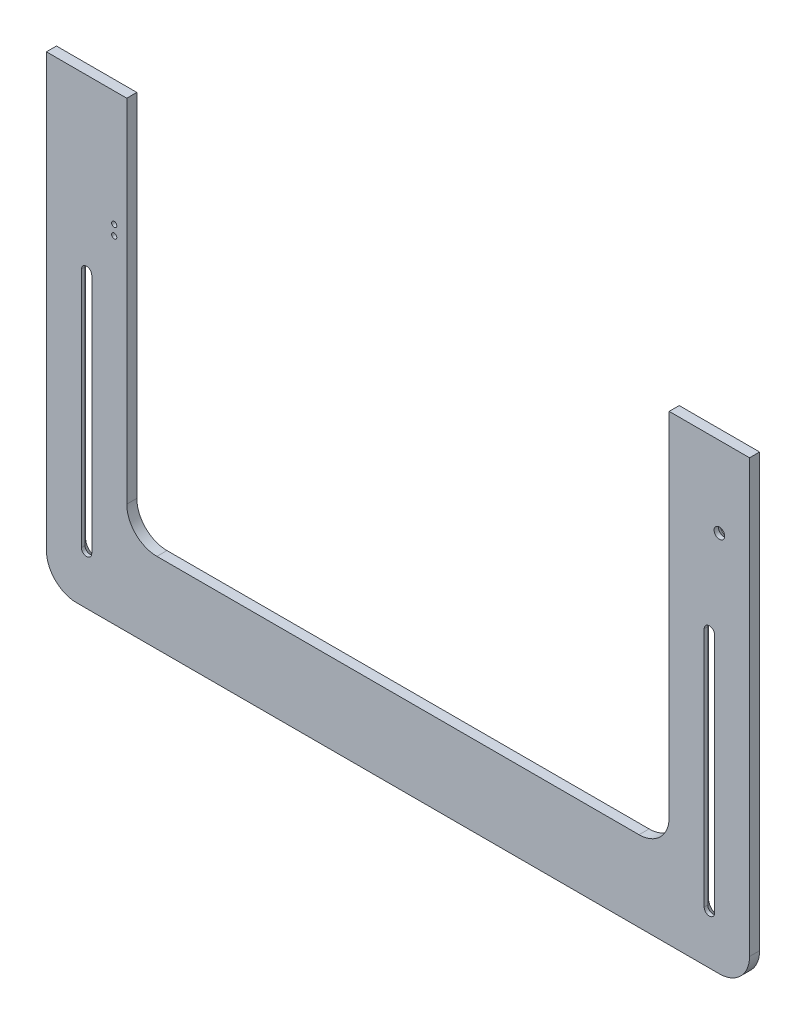
SolidWorks part; units mm, degrees
ref_plane "Front Plane" through (0, 0, 0) normal (0, 0, 1) x (1, 0, 0)
ref_plane "Top Plane" through (0, 0, 0) normal (0, 1, 0) x (1, 0, 0)
ref_plane "Right Plane" through (0, 0, 0) normal (1, 0, 0) x (0, 0, -1)
sketch "Sketch1" plane through (0, 0, 0) normal (0, 0, 1) x (1, 0, 0)
  line L0 (0, 0) -> (0, -292.1)
  line L1 (0, -292.1) -> (444.5, -292.1)
  line L2 (444.5, -292.1) -> (444.5, 0)
  line L3 (444.5, 0) -> (393.7, 0)
  line L4 (393.7, 0) -> (393.7, -241.3)
  line L5 (393.7, -241.3) -> (50.8, -241.3)
  line L6 (50.8, -241.3) -> (50.8, 0)
  line L7 (50.8, 0) -> (0, 0)
  dimension "D1" = 292.1
  dimension "D2" = 444.5
  dimension "D3" = 50.8
  dimension "D4" = 50.8
  dimension "D5" = 241.3
extrude "Boss-Extrude1" add sketch "Sketch1" along normal blind 6.35
fillet "Fillet5" radius 19.05 1 edges at (0, -292.1, 3.175)
fillet "Fillet6" radius 19.05 1 edges at (444.5, -292.1, 3.175)
fillet "Fillet7" radius 19.05 1 edges at (50.8, -241.3, 3.175)
fillet "Fillet8" radius 19.05 1 edges at (393.7, -241.3, 3.175)
sketch "Sketch2" plane through (0, 0, 6.35) normal (0, 0, 1) x (1, 0, 0)
  line L0 (419.1, -107.95) -> (419.1, -260.35) construction
  line L1 (422.3639, -107.95) -> (422.3639, -260.35)
  line L2 (415.8361, -107.95) -> (415.8361, -260.35)
  line L4 (444.5, -273.05) -> (444.5, 0) construction
  line L5 (374.65, -241.3) -> (69.85, -241.3) construction
  arc A0 (422.3639, -107.95) -> (415.8361, -107.95) centre (419.1, -107.95) ccw
  arc A1 (415.8361, -260.35) -> (422.3639, -260.35) centre (419.1, -260.35) ccw
  point P2 (419.1, -184.15)
  dimension "D1" = 25.4
  dimension "D2" = 19.05
extrude "Cut-Extrude1" cut sketch "Sketch2" against normal through all
sketch "Sketch3" plane through (0, 0, 6.35) normal (0, 0, 1) x (1, 0, 0)
  line L0 (25.4, -107.95) -> (25.4, -260.35) construction
  line L1 (28.6639, -107.95) -> (28.6639, -260.35)
  line L2 (22.1361, -107.95) -> (22.1361, -260.35)
  line L3 (0, 0) -> (0, -273.05) construction
  line L4 (374.65, -241.3) -> (69.85, -241.3) construction
  arc A0 (28.6639, -107.95) -> (22.1361, -107.95) centre (25.4, -107.95) ccw
  arc A1 (22.1361, -260.35) -> (28.6639, -260.35) centre (25.4, -260.35) ccw
  point P2 (25.4, -184.15)
  dimension "D1" = 25.4
  dimension "D2" = 19.05
extrude "Cut-Extrude2" cut sketch "Sketch3" against normal through all
hole_wizard "CSK for 1/4 Flat Head Machine Screw1" positions "Sketch5" profile "Sketch4" countersink size "1/4" standard "ANSI Inch" end condition through all
sketch "Sketch5" plane through (0, 0, 0) normal (0, 0, -1) x (-1, 0, 0)
  point P0 (-425.45, -50.8)
sketch "Sketch4" plane through (425.45, -50.8, 0) normal (1, 0, 0) x (0, 1, 0)
  line L0 (0, 0) -> (0, 6.35)
  line L1 (0, 6.35) -> (3.3782, 6.35)
  line L2 (3.3782, 6.35) -> (3.3782, 3.5209)
  line L3 (3.3782, 3.5209) -> (6.4389, 0)
  line L5 (6.4389, 0) -> (0, 0)
  line L6 (-3.3782, 3.5209) -> (-6.4389, 0) construction
  line L11 (0, -6.35) -> (0, 107.95) construction
  dimension "Thru Hole Dia." = 6.7564
  dimension "Thru Hole Depth" = 6.35
  dimension "Near C'Sink Dia." = 12.8778
  dimension "Near C'Sink Angle" = 82
chamfer "Chamfer1" distance 4.0894 angle 42 4 edges at (22.1361, -184.15, 0) (25.4, -263.6139, 0) (25.4, -104.6861, 0) (28.6639, -184.15, 0)
chamfer "Chamfer2" distance 4.0894 angle 42 4 edges at (419.1, -104.6861, 0) (415.8361, -184.15, 0) (419.1, -263.6139, 0) (422.3639, -184.15, 0)
ref_plane "Plane1" through (222.25, 0, 0) normal (1, 0, 0) x (0, 0, -1)
hole_wizard "#62 (0.038) Diameter Hole1" positions "Sketch11" profile "Sketch10" hole size "#62" standard "ANSI Inch"
sketch "Sketch11" plane through (0, 0, 6.35) normal (0, 0, 1) x (1, 0, 0)
  point P0 (42.8625, -73.025)
  point P3 (42.8625, -79.375)
sketch "Sketch10" plane through (42.8625, -73.025, 6.35) normal (1, 0, 0) x (0, -1, 0)
  line L0 (0, 0) -> (0, 25.69)
  line L1 (0, 25.69) -> (0.4826, 25.4)
  line L2 (0.4826, 25.4) -> (0.4826, 0)
  line L5 (0.4826, 0) -> (0, 0)
  line L10 (0, 25.69) -> (-0.4826, 25.4) construction
  line L11 (0, -6.35) -> (0, 107.95) construction
  dimension "Hole Dia." = 0.9652
  dimension "Hole Depth" = 25.4
  dimension "Drill Angle" = 118
hole_wizard "CSK for #4 Flat Head Machine Screw3" positions "Sketch13" profile "Sketch12" countersink size "#4" standard "ANSI Inch" end condition through all
sketch "Sketch13" plane through (0, 0, 0) normal (0, 0, -1) x (-1, 0, 0)
  point P0 (-42.8625, -79.375)
  point P3 (-42.8625, -73.025)
sketch "Sketch12" plane through (42.8625, -79.375, 0) normal (1, 0, 0) x (0, 1, 0)
  line L0 (0, 0) -> (0, 6.35)
  line L1 (0, 6.35) -> (1.6319, 6.35)
  line L2 (1.6319, 6.35) -> (1.6319, 1.4098)
  line L3 (1.6319, 1.4098) -> (2.8575, 0)
  line L5 (2.8575, 0) -> (0, 0)
  line L6 (-1.6319, 1.4098) -> (-2.8575, 0) construction
  line L11 (0, -6.35) -> (0, 107.95) construction
  dimension "Thru Hole Dia." = 3.2639
  dimension "Thru Hole Depth" = 6.35
  dimension "Near C'Sink Dia." = 5.715
  dimension "Near C'Sink Angle" = 82
